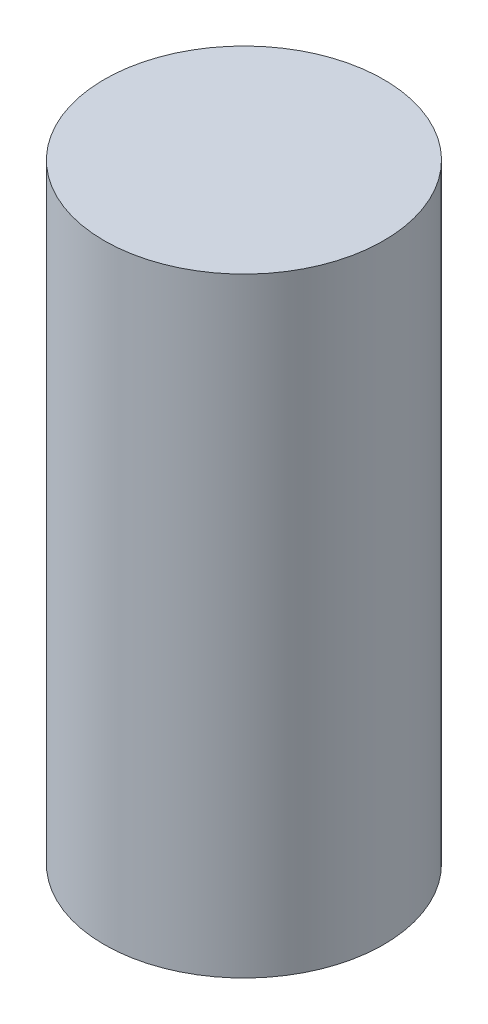
SolidWorks part; units mm, degrees
ref_plane "前视基准面" through (0, 0, 0) normal (0, 0, 1) x (1, 0, 0)
ref_plane "上视基准面" through (0, 0, 0) normal (0, 1, 0) x (1, 0, 0)
ref_plane "右视基准面" through (0, 0, 0) normal (1, 0, 0) x (0, 0, -1)
other "Configuration Table"
sketch "草图1" plane through (0, 0, 0) normal (0, 1, 0) x (1, 0, 0)
  circle A0 centre (0, 0) radius 5.5
  dimension "D1" = 11
extrude "凸台-拉伸1" add sketch "草图1" along normal blind 24
